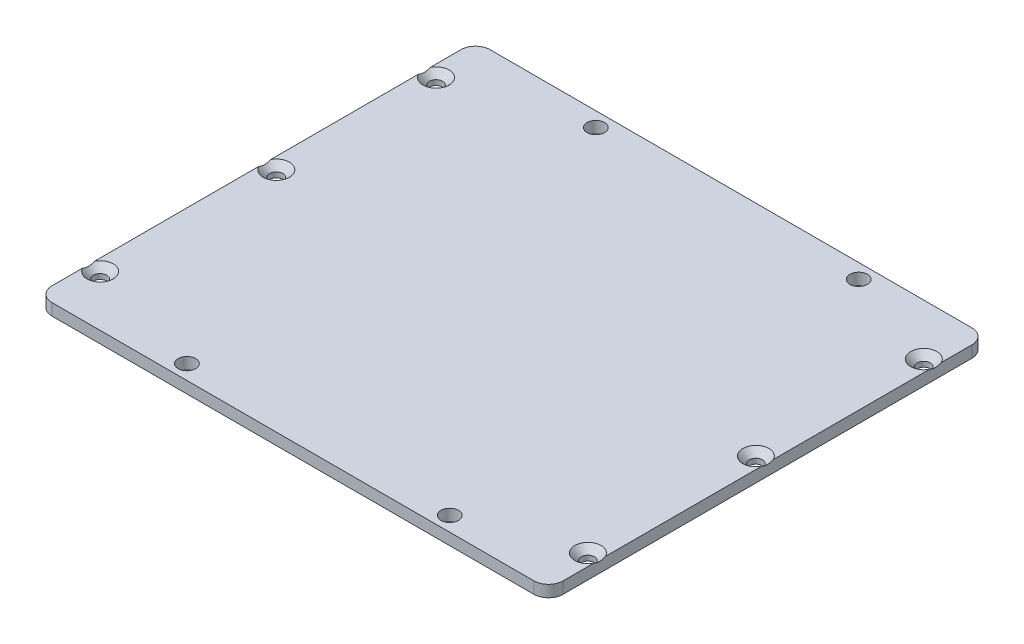
SolidWorks part; units mm, degrees
ref_plane "Ön Düzlem" through (0, 0, 0) normal (0, 0, 1) x (1, 0, 0)
ref_plane "Üst Düzlem" through (0, 0, 0) normal (0, 1, 0) x (1, 0, 0)
ref_plane "Sağ Düzlem" through (0, 0, 0) normal (1, 0, 0) x (0, 0, -1)
sketch "Çizim1" plane through (0, 0, 0) normal (0, 1, 0) x (1, 0, 0)
  line L0 (-87.5, 75) -> (87.5, -75) construction
  line L1 (-87.5, 75) -> (87.5, 75)
  line L2 (-87.5, 75) -> (-87.5, -75)
  line L3 (-87.5, -75) -> (87.5, -75)
  line L4 (87.5, 75) -> (87.5, -75)
  dimension "D1" = 175
  dimension "D2" = 150
extrude "Yükseklik-Ekstrüzyon1" add sketch "Çizim1" along normal blind 4
fillet "Radyus1" radius 5 4 edges at (-87.5, 2, -75) (87.5, 2, -75) (87.5, 2, 75) (-87.5, 2, 75)
sketch "Çizim2" plane through (0, 4, 0) normal (0, 1, 0) x (1, 0, 0)
  line L0 (83.5, -2) -> (83.5, 2) construction
  line L1 (-82.5, -75) -> (82.5, -75) construction
  line L2 (82.5, 75) -> (-82.5, 75) construction
  circle A0 centre (-83.5, -57.5) radius 2
  circle A1 centre (83.5, -57.5) radius 2
  circle A2 centre (83.5, 0) radius 2
  circle A3 centre (83.5, 57.5) radius 2
  circle A4 centre (-83.5, 57.5) radius 2
  circle A5 centre (-83.5, 2.8091) radius 2
  circle A6 centre (-41.3075, -70) radius 3
  circle A7 centre (48.6925, -70) radius 3
  circle A8 centre (-41.3075, 70) radius 3
  circle A9 centre (48.6925, 70) radius 3
  dimension "D1" = 90
  dimension "D2" = 5
  dimension "D3" = 5
extrude "Kes-Ekstrüzyon1" cut sketch "Çizim2" against normal blind 10
hole_wizard "M4 SFHCS İçin Havşa1" positions "Çizim4" profile "Çizim3" countersink size "M4" standard "ANSI Metrik" end condition through all
sketch "Çizim4" plane through (0, 4, 0) normal (0, 1, 0) x (1, 0, 0)
  point P0 (-83.5, 57.5)
  point P3 (-83.5, 2.8091)
  point P6 (-83.5, -57.5)
  point P9 (83.5, -57.5)
  point P12 (83.5, 0)
  point P15 (83.5, 57.5)
sketch "Çizim3" plane through (-83.5, 4, -57.5) normal (1, 0, 0) x (0, 0, 1)
  line L0 (0, 0) -> (0, 4)
  line L1 (0, 4) -> (2.25, 4)
  line L2 (2.25, 4) -> (2.25, 2.23)
  line L3 (2.25, 2.23) -> (4.48, 0)
  line L5 (4.48, 0) -> (0, 0)
  line L6 (-2.25, 2.23) -> (-4.48, 0) construction
  line L11 (0, -6.35) -> (0, 107.95) construction
  dimension "Thru Hole Dia." = 4.5
  dimension "Thru Hole Depth" = 4
  dimension "Near C'Sink Dia." = 8.96
  dimension "Near C'Sink Angle" = 90
